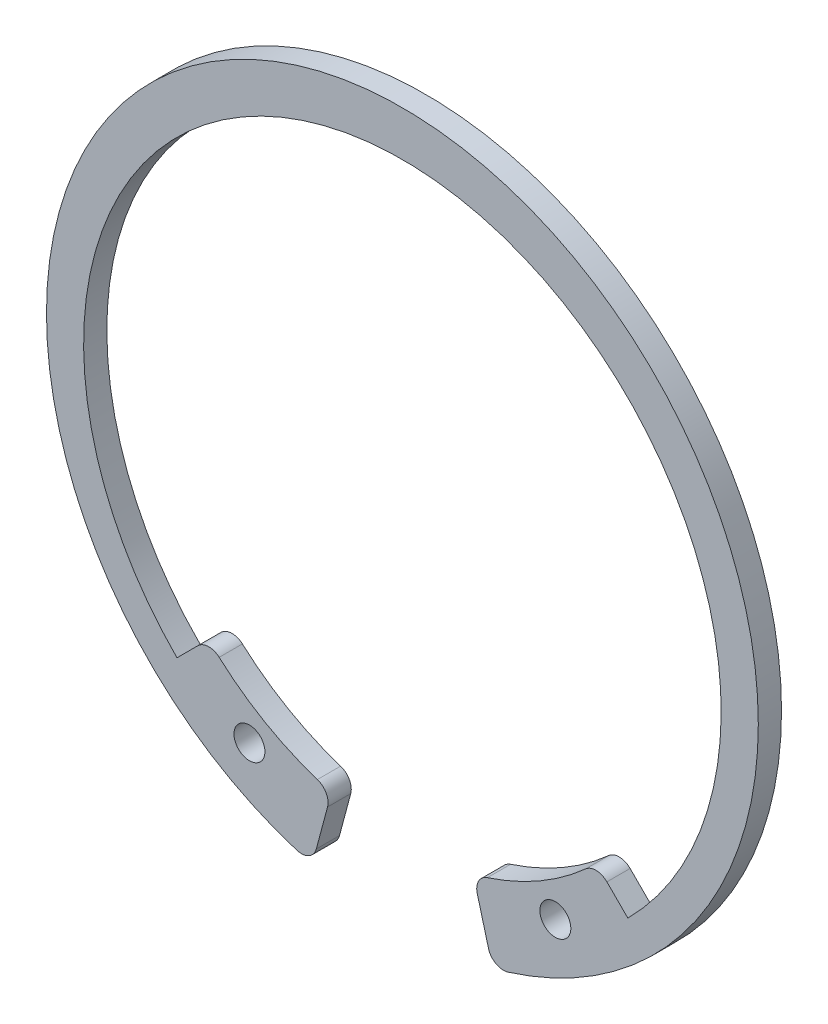
SolidWorks part; units mm, degrees
ref_plane "Plan1" through (0, 0, 0) normal (0, 0, 1) x (1, 0, 0)
ref_plane "Plan2" through (0, 0, 0) normal (0, 1, 0) x (1, 0, 0)
ref_plane "Plan3" through (0, 0, 0) normal (1, 0, 0) x (0, 0, -1)
sketch "Esquisse1" plane through (0, 0, 0) normal (0, 0, 1) x (1, 0, 0)
  line L0 (-5.3317, 19.8981) -> (2.0576, -7.6791) construction
  line L1 (0, 0) -> (0, -67.082) construction
  line L2 (5.5646, -20.7672) -> (4.8373, -18.0531)
  line L3 (0, 0) -> (7, -7) construction
  line L4 (13.2158, -13.2158) -> (14.5664, -14.5664)
  line L5 (-5.5646, -20.7672) -> (-4.8373, -18.0531)
  line L6 (-13.2158, -13.2158) -> (-14.5664, -14.5664)
  line L7 (0, 0) -> (0, 20.6) construction
  line L8 (0, 20.6) -> (0, 23.5) construction
  line L9 (-5.2009, -19.4102) -> (-14.5664, -14.5664) construction
  arc A0 (14.5664, -14.5664) -> (-14.5664, -14.5664) centre (0, 0) ccw
  arc A1 (-11.8404, -13.179) -> (-5.4932, -16.8436) centre (0, 0) ccw
  arc A2 (6.8273, -21.4633) -> (-6.8273, -21.4633) centre (0, 0.5) ccw
  arc A4 (5.4932, -16.8436) -> (11.8404, -13.179) centre (0, 0) ccw
  arc A5 (11.8404, -13.179) -> (13.2158, -13.2158) centre (12.5087, -13.9229) cw
  arc A6 (4.8373, -18.0531) -> (5.4932, -16.8436) centre (5.8032, -17.7943) cw
  arc A7 (-4.8373, -18.0531) -> (-5.4932, -16.8436) centre (-5.8032, -17.7943) ccw
  arc A8 (-13.2158, -13.2158) -> (-11.8404, -13.179) centre (-12.5087, -13.9229) cw
  arc A9 (-6.8273, -21.4633) -> (-5.5646, -20.7672) centre (-6.5305, -20.5084) ccw
  arc A10 (6.8273, -21.4633) -> (5.5646, -20.7672) centre (6.5305, -20.5084) cw
  circle A11 centre (-9.8837, -16.9883) radius 1
  circle A12 centre (9.8837, -16.9883) radius 1
  point P19 (12.5276, -12.5276)
  point P22 (4.5854, -17.113)
  point P25 (-4.5854, -17.113)
  point P30 (-12.5276, -12.5276)
  point P33 (-5.8277, -21.7494)
  point P36 (5.8277, -21.7494)
  dimension "D1" = 23
  dimension "D2" = 4.8
  dimension "D3" = 2.9
  dimension "D6" = 1
  dimension "D4" = 0.5
  dimension "D7" = 2
  dimension "D5" = 30
  dimension "a" = 15
extrude "Base-Extrusion" add sketch "Esquisse1" along normal blind 1.5
equation "\"D5@Esquisse1\"=\"a@Esquisse1\"*2"
equation "\"D6@Esquisse1\"=\"D7@Esquisse1\"/2"
equation "\"D4@Esquisse1\" = \"D6@Esquisse1\"/2"
